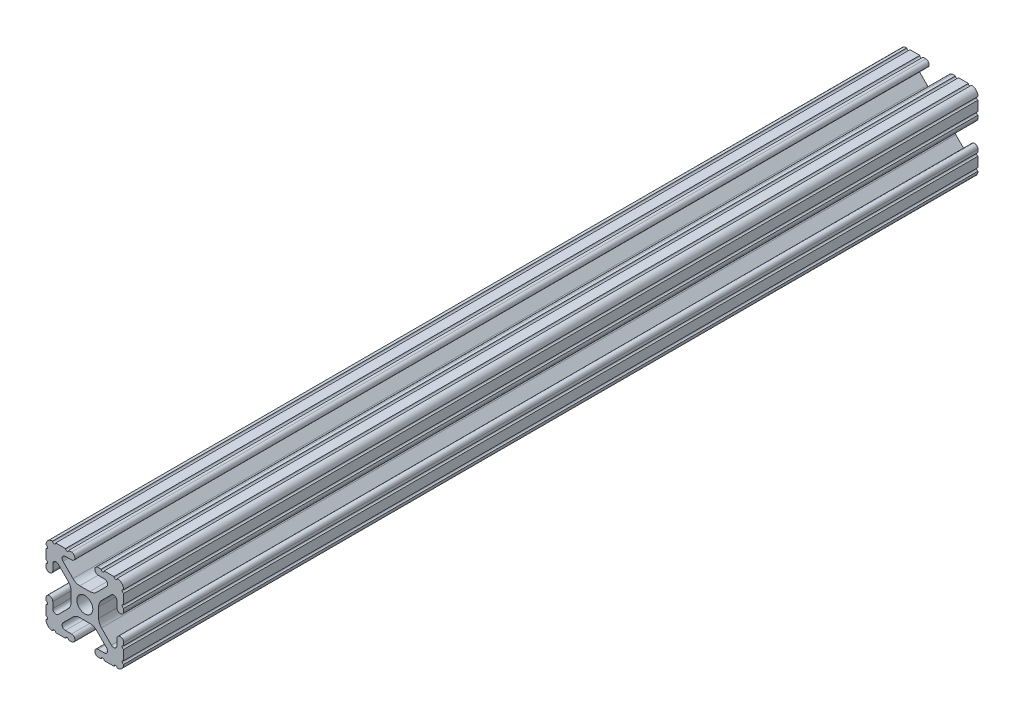
SolidWorks part; units mm, degrees
material "6105-T5 Aluminum"
ref_plane "Front Plane" through (0, 0, 0) normal (0, 0, 1) x (1, 0, 0)
ref_plane "Top Plane" through (0, 0, 0) normal (0, 1, 0) x (1, 0, 0)
ref_plane "Right Plane" through (0, 0, 0) normal (1, 0, 0) x (0, 0, -1)
sketch "Sketch1" plane through (0, 0, 0) normal (0, 0, 1) x (1, 0, 0)
  line L0 (10.5918, 12.7) -> (10.5664, 12.7)
  line L1 (9.5504, 12.7) -> (6.3246, 12.7)
  line L2 (5.3086, 12.7) -> (4.3561, 12.7)
  line L3 (4.3561, 10.4902) -> (6.3701, 10.4902)
  line L4 (7.1192, 8.6817) -> (3.8846, 5.4471)
  line L5 (1.6396, 4.5172) -> (-1.6396, 4.5172)
  line L6 (-3.8846, 5.4471) -> (-7.1192, 8.6817)
  line L7 (-6.3701, 10.4902) -> (-4.3561, 10.4902)
  line L8 (-4.3561, 12.7) -> (-5.3086, 12.7)
  line L9 (-6.3246, 12.7) -> (-9.5504, 12.7)
  line L10 (-10.5664, 12.7) -> (-10.5918, 12.7)
  line L11 (-12.7, 10.5918) -> (-12.7, 10.5664)
  line L12 (-12.7, 9.5504) -> (-12.7, 6.3246)
  line L13 (-12.7, 5.3086) -> (-12.7, 4.3561)
  line L14 (-10.4902, 4.3561) -> (-10.4902, 6.3701)
  line L15 (-8.6817, 7.1192) -> (-5.4471, 3.8846)
  line L16 (-4.5172, 1.6396) -> (-4.5172, -1.6396)
  line L17 (-5.4471, -3.8846) -> (-8.6817, -7.1192)
  line L18 (-10.4902, -6.3701) -> (-10.4902, -4.3561)
  line L19 (-12.7, -4.3561) -> (-12.7, -5.3086)
  line L20 (-12.7, -6.3246) -> (-12.7, -9.5504)
  line L21 (-12.7, -10.5664) -> (-12.7, -10.5918)
  line L22 (-10.5918, -12.7) -> (-10.5664, -12.7)
  line L23 (-9.5504, -12.7) -> (-6.3246, -12.7)
  line L24 (-5.3086, -12.7) -> (-4.3561, -12.7)
  line L25 (-4.3561, -10.4902) -> (-6.3701, -10.4902)
  line L26 (-7.1192, -8.6817) -> (-3.8846, -5.4471)
  line L27 (-1.6396, -4.5172) -> (1.6396, -4.5172)
  line L28 (3.8846, -5.4471) -> (7.1192, -8.6817)
  line L29 (6.3701, -10.4902) -> (4.3561, -10.4902)
  line L30 (4.3561, -12.7) -> (5.3086, -12.7)
  line L31 (6.3246, -12.7) -> (9.5504, -12.7)
  line L32 (10.5664, -12.7) -> (10.5918, -12.7)
  line L33 (12.7, -10.5918) -> (12.7, -10.5664)
  line L34 (12.7, -9.5504) -> (12.7, -6.3246)
  line L35 (12.7, -5.3086) -> (12.7, -4.3561)
  line L36 (10.4902, -4.3561) -> (10.4902, -6.3701)
  line L37 (8.6817, -7.1192) -> (5.4471, -3.8846)
  line L38 (4.5172, -1.6396) -> (4.5172, 1.6396)
  line L39 (5.4471, 3.8846) -> (8.6817, 7.1192)
  line L40 (10.4902, 6.3701) -> (10.4902, 4.3561)
  line L41 (12.7, 4.3561) -> (12.7, 5.3086)
  line L42 (12.7, 6.3246) -> (12.7, 9.5504)
  line L43 (12.7, 10.5664) -> (12.7, 10.5918)
  circle A0 centre (0, 0) radius 2.6035
  arc A1 (12.7, 10.5918) -> (10.5918, 12.7) centre (10.5918, 10.5918) ccw
  arc A2 (9.5504, 12.7) -> (10.5664, 12.7) centre (10.0584, 12.7) ccw
  arc A3 (5.3086, 12.7) -> (6.3246, 12.7) centre (5.8166, 12.7) ccw
  arc A4 (4.3561, 12.7) -> (4.3561, 10.4902) centre (4.3561, 11.5951) ccw
  arc A5 (7.1192, 8.6817) -> (6.3701, 10.4902) centre (6.3701, 9.4308) ccw
  arc A6 (1.6396, 4.5172) -> (3.8846, 5.4471) centre (1.6396, 7.6922) ccw
  arc A7 (-3.8846, 5.4471) -> (-1.6396, 4.5172) centre (-1.6396, 7.6922) ccw
  arc A8 (-6.3701, 10.4902) -> (-7.1192, 8.6817) centre (-6.3701, 9.4308) ccw
  arc A9 (-4.3561, 10.4902) -> (-4.3561, 12.7) centre (-4.3561, 11.5951) ccw
  arc A10 (-6.3246, 12.7) -> (-5.3086, 12.7) centre (-5.8166, 12.7) ccw
  arc A11 (-10.5664, 12.7) -> (-9.5504, 12.7) centre (-10.0584, 12.7) ccw
  arc A12 (-10.5918, 12.7) -> (-12.7, 10.5918) centre (-10.5918, 10.5918) ccw
  arc A13 (-12.7, 9.5504) -> (-12.7, 10.5664) centre (-12.7, 10.0584) ccw
  arc A14 (-12.7, 5.3086) -> (-12.7, 6.3246) centre (-12.7, 5.8166) ccw
  arc A15 (-12.7, 4.3561) -> (-10.4902, 4.3561) centre (-11.5951, 4.3561) ccw
  arc A16 (-8.6817, 7.1192) -> (-10.4902, 6.3701) centre (-9.4308, 6.3701) ccw
  arc A17 (-4.5172, 1.6396) -> (-5.4471, 3.8846) centre (-7.6922, 1.6396) ccw
  arc A18 (-5.4471, -3.8846) -> (-4.5172, -1.6396) centre (-7.6922, -1.6396) ccw
  arc A19 (-10.4902, -6.3701) -> (-8.6817, -7.1192) centre (-9.4308, -6.3701) ccw
  arc A20 (-10.4902, -4.3561) -> (-12.7, -4.3561) centre (-11.5951, -4.3561) ccw
  arc A21 (-12.7, -6.3246) -> (-12.7, -5.3086) centre (-12.7, -5.8166) ccw
  arc A22 (-12.7, -10.5664) -> (-12.7, -9.5504) centre (-12.7, -10.0584) ccw
  arc A23 (-12.7, -10.5918) -> (-10.5918, -12.7) centre (-10.5918, -10.5918) ccw
  arc A24 (-9.5504, -12.7) -> (-10.5664, -12.7) centre (-10.0584, -12.7) ccw
  arc A25 (-5.3086, -12.7) -> (-6.3246, -12.7) centre (-5.8166, -12.7) ccw
  arc A26 (-4.3561, -12.7) -> (-4.3561, -10.4902) centre (-4.3561, -11.5951) ccw
  arc A27 (-7.1192, -8.6817) -> (-6.3701, -10.4902) centre (-6.3701, -9.4308) ccw
  arc A28 (-1.6396, -4.5172) -> (-3.8846, -5.4471) centre (-1.6396, -7.6922) ccw
  arc A29 (3.8846, -5.4471) -> (1.6396, -4.5172) centre (1.6396, -7.6922) ccw
  arc A30 (6.3701, -10.4902) -> (7.1192, -8.6817) centre (6.3701, -9.4308) ccw
  arc A31 (4.3561, -10.4902) -> (4.3561, -12.7) centre (4.3561, -11.5951) ccw
  arc A32 (6.3246, -12.7) -> (5.3086, -12.7) centre (5.8166, -12.7) ccw
  arc A33 (10.5664, -12.7) -> (9.5504, -12.7) centre (10.0584, -12.7) ccw
  arc A34 (10.5918, -12.7) -> (12.7, -10.5918) centre (10.5918, -10.5918) ccw
  arc A35 (12.7, -9.5504) -> (12.7, -10.5664) centre (12.7, -10.0584) ccw
  arc A36 (12.7, -5.3086) -> (12.7, -6.3246) centre (12.7, -5.8166) ccw
  arc A37 (12.7, -4.3561) -> (10.4902, -4.3561) centre (11.5951, -4.3561) ccw
  arc A38 (8.6817, -7.1192) -> (10.4902, -6.3701) centre (9.4308, -6.3701) ccw
  arc A39 (4.5172, -1.6396) -> (5.4471, -3.8846) centre (7.6922, -1.6396) ccw
  arc A40 (5.4471, 3.8846) -> (4.5172, 1.6396) centre (7.6922, 1.6396) ccw
  arc A41 (10.4902, 6.3701) -> (8.6817, 7.1192) centre (9.4308, 6.3701) ccw
  arc A42 (10.4902, 4.3561) -> (12.7, 4.3561) centre (11.5951, 4.3561) ccw
  arc A43 (12.7, 6.3246) -> (12.7, 5.3086) centre (12.7, 5.8166) ccw
  arc A44 (12.7, 10.5664) -> (12.7, 9.5504) centre (12.7, 10.0584) ccw
extrude "Boss-Extrude1" add sketch "Sketch1" along normal blind 279.4
